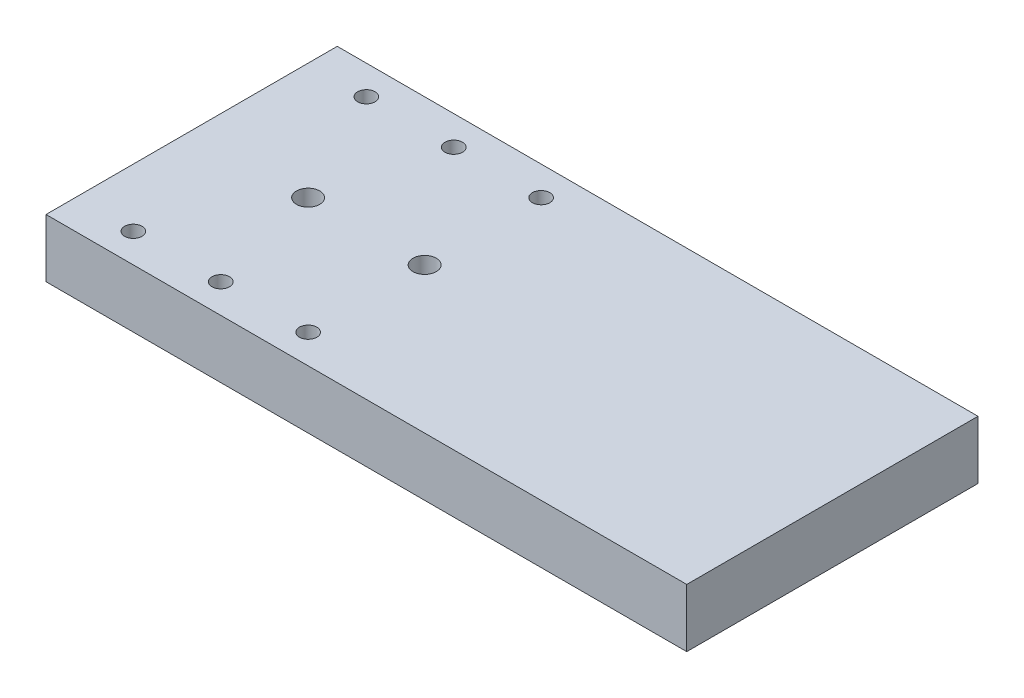
SolidWorks part; units mm, degrees
material "Сосна"
ref_plane "Спереди" through (0, 0, 0) normal (0, 0, 1) x (1, 0, 0)
ref_plane "Сверху" through (0, 0, 0) normal (0, 1, 0) x (1, 0, 0)
ref_plane "Справа" through (0, 0, 0) normal (1, 0, 0) x (0, 0, -1)
sketch "Эскиз1" plane through (0, 0, 0) normal (0, 1, 0) x (1, 0, 0)
  line L1 (0, 0) -> (220, 0)
  line L2 (0, 0) -> (0, 100)
  line L3 (0, 100) -> (220, 100)
  line L4 (220, 0) -> (220, 100)
  dimension "D1" = 220
  dimension "D2" = 100
extrude "Бобышка-Вытянуть1" add sketch "Эскиз1" along normal blind 20
sketch "Эскиз2" plane through (0, 20, 0) normal (0, 1, 0) x (1, 0, 0)
  line L0 (0, 50) -> (220, 50) construction
  line L1 (0, 100) -> (0, 0) construction
  line L2 (220, 0) -> (220, 100) construction
  line L3 (0, 90) -> (220, 90) construction
  line L4 (0, 10) -> (220, 10) construction
  line L5 (0, 0) -> (220, 0) construction
  line L6 (220, 100) -> (0, 100) construction
  circle A0 centre (80, 50) radius 4
  circle A1 centre (40, 50) radius 4
  circle A2 centre (20, 90) radius 2
  circle A3 centre (50, 90) radius 2
  circle A4 centre (80, 90) radius 2
  circle A5 centre (20, 10) radius 2
  circle A6 centre (50, 10) radius 2
  circle A7 centre (80, 10) radius 2
  dimension "D2" = 40
  dimension "D5" = 20
  dimension "D11" = 4
  dimension "D12" = 4
  dimension "D13" = 4
  dimension "D14" = 8
  dimension "D15" = 8
  dimension "D16" = 4
  dimension "D17" = 4
  dimension "D18" = 4
  dimension "D3" = 10
  dimension "D4" = 10
  dimension "D6" = 50
  dimension "D7" = 80
  dimension "D8" = 20
  dimension "D9" = 50
  dimension "D10" = 80
  dimension "D19" = 40
extrude "Вырез-Вытянуть1" cut sketch "Эскиз2" against normal blind 10 contours A0 | A1
sketch "Эскиз3" plane through (0, 20, 0) normal (0, 1, 0) x (1, 0, 0)
  line L0 (0, 90) -> (220, 90) construction
  line L1 (0, 100) -> (0, 0) construction
  line L2 (220, 0) -> (220, 100) construction
  line L3 (0, 10) -> (220, 10) construction
  line L4 (220, 100) -> (0, 100) construction
  line L5 (0, 0) -> (220, 0) construction
  circle A0 centre (20, 90) radius 3
  circle A1 centre (50, 90) radius 3
  circle A2 centre (80, 90) radius 3
  circle A3 centre (20, 10) radius 3
  circle A4 centre (50, 10) radius 3
  circle A5 centre (80, 10) radius 3
  dimension "D3" = 20
  dimension "D9" = 6
  dimension "D10" = 6
  dimension "D11" = 6
  dimension "D12" = 6
  dimension "D13" = 6
  dimension "D14" = 6
  dimension "D1" = 10
  dimension "D2" = 10
  dimension "D4" = 50
  dimension "D5" = 80
  dimension "D6" = 20
  dimension "D7" = 50
  dimension "D8" = 80
extrude "Вырез-Вытянуть2" cut sketch "Эскиз3" against normal blind 20
sketch "Эскиз4" plane through (0, 0, 0) normal (0, -1, 0) x (1, 0, 0)
  line L0 (220, 0) -> (220, -100) construction
  line L3 (220, -100) -> (0, -100) construction
  line L6 (0, 0) -> (220, 0) construction
  circle A0 centre (210, -10) radius 3
  circle A1 centre (110, -10) radius 3
  circle A2 centre (210, -90) radius 3
  circle A3 centre (110, -90) radius 3
  dimension "D3" = 10
  dimension "D5" = 10
  dimension "D7" = 6
  dimension "D8" = 6
  dimension "D9" = 6
  dimension "D10" = 6
  dimension "D2" = 10
  dimension "D4" = 10
